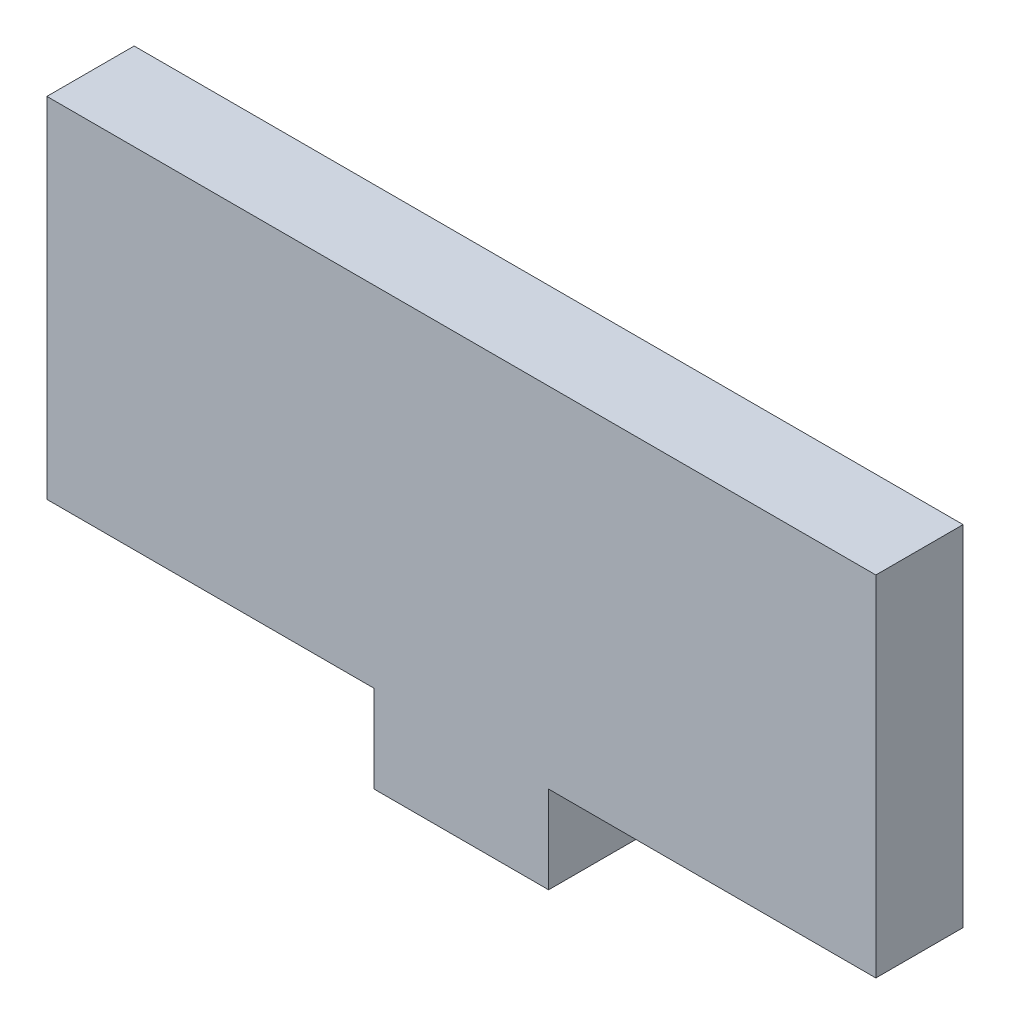
SolidWorks part; units mm, degrees
ref_plane "Front Plane" through (0, 0, 0) normal (0, 0, 1) x (1, 0, 0)
ref_plane "Top Plane" through (0, 0, 0) normal (0, 1, 0) x (1, 0, 0)
ref_plane "Right Plane" through (0, 0, 0) normal (1, 0, 0) x (0, 0, -1)
sketch "Sketch2" plane through (0, 0, 0) normal (0, 0, 1) x (1, 0, 0)
  line L1 (0, 0) -> (60.325, 0)
  line L2 (0, 0) -> (0, 25.4)
  line L3 (0, 25.4) -> (60.325, 25.4)
  line L4 (60.325, 0) -> (60.325, 25.4)
  line L5 (23.8125, 0) -> (36.5125, 0)
  line L6 (23.8125, 0) -> (23.8125, -6.35)
  line L7 (23.8125, -6.35) -> (36.5125, -6.35)
  line L8 (36.5125, 0) -> (36.5125, -6.35)
  point P9 (30.1625, 0)
  dimension "D1" = 60.325
  dimension "D2" = 25.4
  dimension "D3" = 12.7
  dimension "D4" = 6.35
  dimension "D5" = 6.35
extrude "Boss-Extrude1" add sketch "Sketch2" along normal blind 6.35 contours L8 L1 L6 L7 | L1 L4 L3 L2
